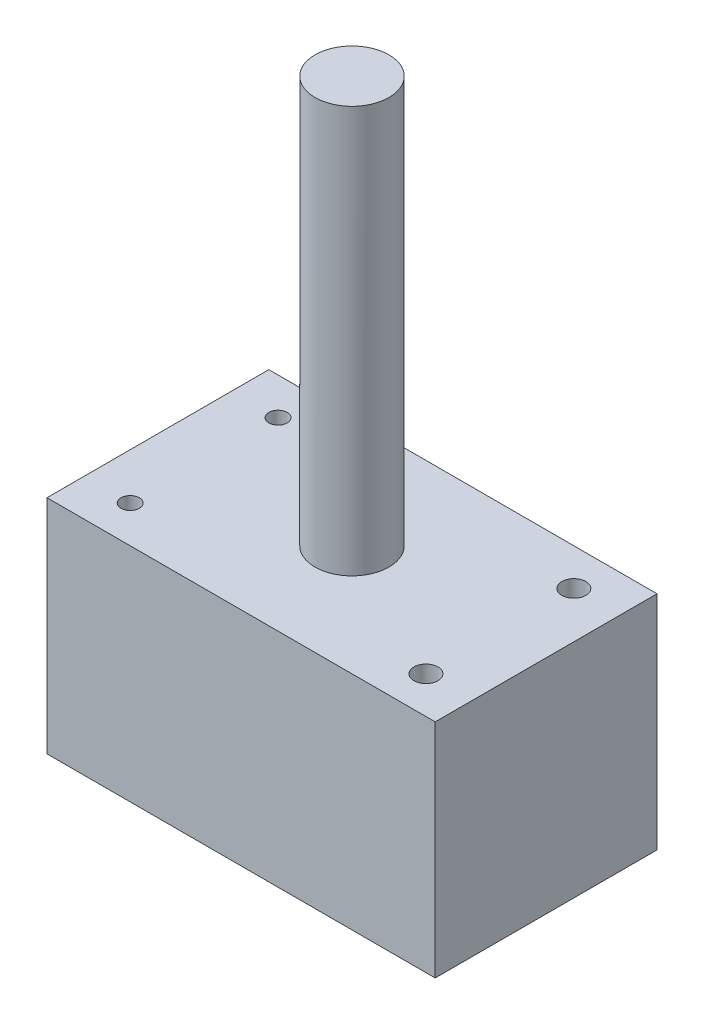
SolidWorks part; units mm, degrees
ref_plane "前视基准面" through (0, 0, 0) normal (0, 0, 1) x (1, 0, 0)
ref_plane "上视基准面" through (0, 0, 0) normal (0, 1, 0) x (1, 0, 0)
ref_plane "右视基准面" through (0, 0, 0) normal (1, 0, 0) x (0, 0, -1)
other "Configuration Table"
sketch "01_Housing_Profile" plane through (0, 0, 0) normal (0, 1, 0) x (1, 0, 0)
  line L1 (-52.5, -30) -> (52.5, -30)
  line L2 (-52.5, -30) -> (-52.5, 30)
  line L3 (-52.5, 30) -> (52.5, 30)
  line L4 (52.5, -30) -> (52.5, 30)
  line L5 (-52.5, -30) -> (52.5, 30) construction
  line L6 (-52.5, 30) -> (52.5, -30) construction
  circle A0 centre (-40, -20) radius 2.4807
  circle A1 centre (40, -20) radius 3.25
  circle A2 centre (-40, 20) radius 2.4807
  circle A3 centre (40, 20) radius 3.25
  point P0 (0, 0)
extrude "01_Housing_Block" add sketch "01_Housing_Profile" along normal blind 60
sketch "03_Output_Shaft_Profile" plane through (0, 0, 0) normal (0, 1, 0) x (1, 0, 0)
  circle A0 centre (0, 0) radius 10
extrude "03_Output_Shaft" add sketch "03_Output_Shaft_Profile" along normal blind 170
